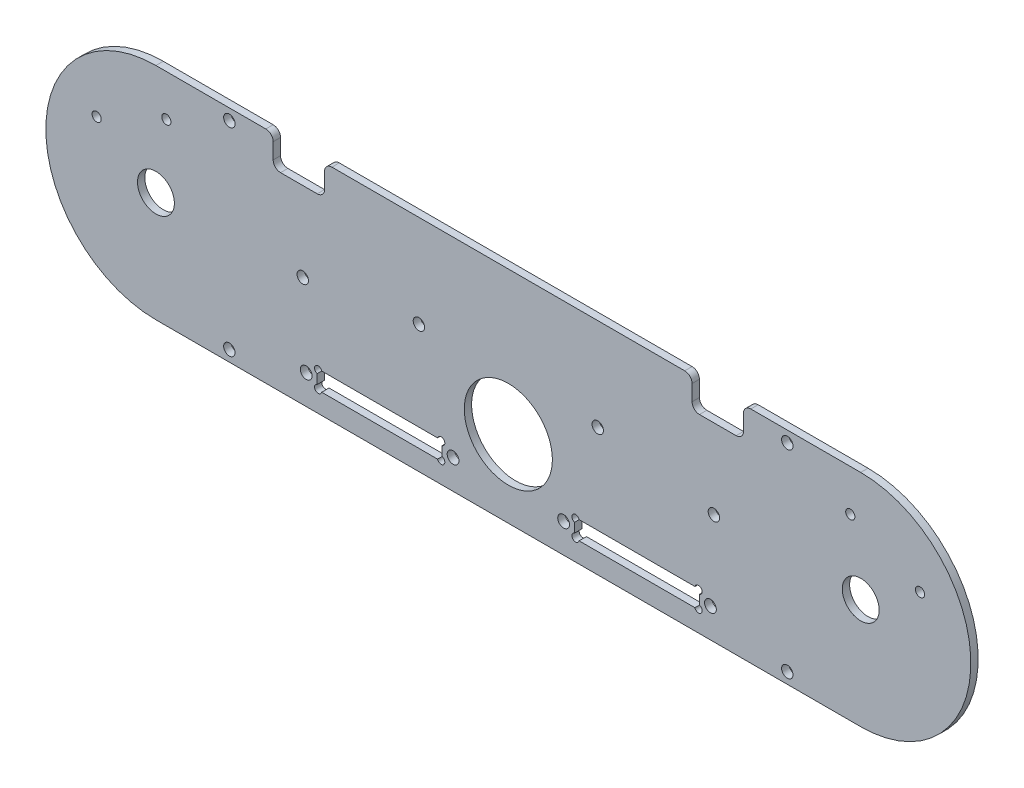
SolidWorks part; units mm, degrees
material "5052-O"
ref_plane "正面" through (0, 0, 0) normal (0, 0, 1) x (1, 0, 0)
ref_plane "平面" through (0, 0, 0) normal (0, 1, 0) x (1, 0, 0)
ref_plane "右側面" through (0, 0, 0) normal (1, 0, 0) x (0, 0, -1)
sketch "ｽｹｯﾁ1" plane through (0, 0, 0) normal (0, 0, 1) x (1, 0, 0)
  line L0 (-96, 0) -> (96, 0) construction
  line L1 (-96, 30) -> (96, 30) construction
  line L2 (-96, -30) -> (96, -30) construction
  line L4 (-96, -30) -> (96, -30)
  line L6 (96, 30) -> (-96, 30)
  arc A0 (-96, 30) -> (-96, -30) centre (-96, 0) ccw construction
  arc A1 (96, -30) -> (96, 30) centre (96, 0) ccw construction
  arc A2 (-96, 30) -> (-96, -30) centre (-96, 0) ccw
  arc A3 (96, -30) -> (96, 30) centre (96, 0) ccw
  point P2 (0, 0)
  dimension "D1" = 30
  dimension "D2" = 192
extrude "ﾎﾞｽ - 押し出し1" add sketch "ｽｹｯﾁ1" along normal blind 2
sketch "ｽｹｯﾁ2" plane through (0, 0, 2) normal (0, 0, 1) x (1, 0, 0)
  line L0 (-96, 0) -> (-56, 0) construction
  line L1 (0, 30) -> (0, -30) construction
  line L2 (-56, 0) -> (0, 0) construction
  line L3 (-96, 0) -> (-102.6562, 14.2743) construction
  line L4 (-76, 30) -> (-76, -30) construction
  line L9 (-112.1521, 9.8464) -> (-93.1604, 18.7023) construction
  line L10 (96, 0) -> (102.6562, 14.2743) construction
  line L11 (96, 30) -> (-96, 30) construction
  line L12 (-96, -30) -> (96, -30) construction
  line L13 (112.1521, 9.8464) -> (93.1604, 18.7023) construction
  line L14 (-96, -30) -> (96, -30) construction
  circle A1 centre (-56, 0) radius 16 construction
  circle A3 centre (-96, 0) radius 24 construction
  circle A8 centre (-56, 0) radius 1.55
  circle A9 centre (-96, 0) radius 11.5 construction
  circle A15 centre (56, 0) radius 1.55
  circle A16 centre (96, 0) radius 11.5 construction
  circle A17 centre (-76, 27) radius 1.55
  circle A18 centre (-76, -27) radius 1.55
  circle A19 centre (76, 27) radius 1.55
  circle A20 centre (76, -27) radius 1.55
  circle A21 centre (-24.3623, 4.8014) radius 16 construction
  circle A22 centre (-24.3623, 4.8014) radius 1.55
  circle A23 centre (24.3623, 4.8014) radius 1.55
  circle A25 centre (0, -9) radius 12
  circle A26 centre (-96, 0) radius 5.025
  circle A27 centre (96, 0) radius 5.025
  circle A28 centre (-112.1521, 9.8464) radius 1.25
  circle A29 centre (-93.1604, 18.7023) radius 1.25
  circle A30 centre (93.1604, 18.7023) radius 1.25
  circle A31 centre (112.1521, 9.8464) radius 1.25
  point P35 (0, 0)
  dimension "D1" = 48
  dimension "D2" = 32
  dimension "D3" = 10.05
  dimension "D5" = 20.955
  dimension "D6" = 23
  dimension "D10" = 3.1
  dimension "D11" = 3.1
  dimension "D12" = 3
  dimension "D13" = 3
  dimension "D8" = 24
  dimension "D17" = 2.5
  dimension "D18" = 21
  dimension "D14" = 20
  dimension "D15" = 96
  dimension "D16" = 25
  dimension "D9" = 15.75
extrude "ｶｯﾄ - 押し出し1" cut sketch "ｽｹｯﾁ2" against normal through all
sketch "ｽｹｯﾁ3" plane through (0, 0, 2) normal (0, 0, 1) x (1, 0, 0)
  line L0 (-55.0573, 24) -> (0, 24) construction
  line L1 (0, 30) -> (0, -28) construction
  line L2 (-18.0573, 26.5) -> (-52.0573, 26.5) construction
  line L3 (-18.0573, 26.5) -> (-18.0573, 21.5) construction
  line L4 (-18.0573, 21.5) -> (-52.0573, 21.5) construction
  line L5 (-52.0573, 26.5) -> (-52.0573, 21.5) construction
  line L6 (-18.0573, 26.5) -> (-52.0573, 21.5) construction
  line L7 (-18.0573, 21.5) -> (-52.0573, 26.5) construction
  line L8 (96, 30) -> (-96, 30) construction
  line L9 (18.0573, 21.5) -> (52.0573, 26.5) construction
  line L10 (18.0573, 26.5) -> (52.0573, 21.5) construction
  line L11 (55.0573, 24) -> (0, 24) construction
  line L12 (52.0573, 26.5) -> (52.0573, 21.5) construction
  line L13 (18.0573, 21.5) -> (52.0573, 21.5) construction
  line L14 (18.0573, 26.5) -> (18.0573, 21.5) construction
  line L15 (18.0573, 26.5) -> (52.0573, 26.5) construction
  line L16 (-125.9833, 1) -> (125.9833, 1) construction
  line L17 (55.0573, -22) -> (0, -22) construction
  line L18 (18.0573, -24.5) -> (52.0573, -19.5) construction
  line L19 (18.0573, -19.5) -> (52.0573, -24.5) construction
  line L20 (-18.0573, -19.5) -> (-52.0573, -24.5) construction
  line L21 (-18.0573, -24.5) -> (-52.0573, -19.5) construction
  line L22 (-55.0573, -22) -> (0, -22) construction
  line L23 (18.0573, -24.5) -> (52.0573, -24.5)
  line L24 (18.0573, -24.5) -> (18.0573, -19.5)
  line L25 (18.0573, -19.5) -> (52.0573, -19.5)
  line L26 (52.0573, -24.5) -> (52.0573, -19.5)
  line L27 (-52.0573, -24.5) -> (-52.0573, -19.5)
  line L28 (-18.0573, -19.5) -> (-52.0573, -19.5)
  line L29 (-18.0573, -24.5) -> (-18.0573, -19.5)
  line L30 (-18.0573, -24.5) -> (-52.0573, -24.5)
  circle A0 centre (-15.0573, 24) radius 1.6 construction
  circle A1 centre (-55.0573, 24) radius 1.6 construction
  circle A2 centre (15.0573, 24) radius 1.6 construction
  circle A3 centre (55.0573, 24) radius 1.6 construction
  circle A4 centre (55.0573, -22) radius 1.6
  circle A5 centre (15.0573, -22) radius 1.6
  circle A6 centre (-55.0573, -22) radius 1.6
  circle A7 centre (-15.0573, -22) radius 1.6
  arc A10 (-96, 30) -> (-96, -30) centre (-96, 0) ccw construction
  arc A11 (96, -30) -> (96, 30) centre (96, 0) ccw construction
  point P2 (-35.0573, 24)
  point P19 (35.0573, 24)
  point P39 (0, 1)
  point P46 (35.0573, -22)
  point P47 (-35.0573, -22)
  dimension "D6" = 3
  dimension "D7" = 3.2
  dimension "D4" = 30.1146
  dimension "D1" = 5
  dimension "D2" = 3
  dimension "D3" = 34
  dimension "D5" = 6
  dimension "D8" = 29
extrude "ｶｯﾄ - 押し出し2" cut sketch "ｽｹｯﾁ3" against normal through all
sketch "ｽｹｯﾁ4" plane through (0, 0, 2) normal (0, 0, 1) x (1, 0, 0)
  line L0 (0, 30) -> (0, 0) construction
  line L1 (-50.0573, 21.7) -> (-64.0573, 21.7)
  line L2 (-50.0573, 21.7) -> (-50.0573, 30)
  line L3 (-50.0573, 30) -> (-64.0573, 30)
  line L4 (-64.0573, 21.7) -> (-64.0573, 30)
  line L5 (-50.0573, 21.7) -> (-64.0573, 30) construction
  line L6 (-50.0573, 30) -> (-64.0573, 21.7) construction
  line L7 (96, 30) -> (-96, 30) construction
  line L8 (50.0573, 30) -> (64.0573, 30)
  line L9 (64.0573, 21.7) -> (64.0573, 30)
  line L10 (50.0573, 21.7) -> (64.0573, 21.7)
  line L11 (50.0573, 21.7) -> (50.0573, 30)
  point P0 (-57.0573, 25.85)
  dimension "D1" = 128.1146
  dimension "D2" = 14
  dimension "D3" = 8.3
extrude "ｶｯﾄ - 押し出し3" cut sketch "ｽｹｯﾁ4" against normal through all
fillet "ﾌｨﾚｯﾄ1" radius 2 8 edges at (64.0573, 30, 1) (64.0573, 21.7, 1) (50.0573, 21.7, 1) (50.0573, 30, 1) (-50.0573, 30, 1) (-50.0573, 21.7, 1) (-64.0573, 21.7, 1) (-64.0573, 30, 1)
sketch "ｽｹｯﾁ5" plane through (0, 0, 2) normal (0, 0, 1) x (1, 0, 0)
  line L0 (-52.0573, -19.5) -> (-18.0573, -24.5) construction
  line L1 (-18.0573, -19.5) -> (-52.0573, -19.5) construction
  line L2 (-18.3073, -19.75) -> (-51.8073, -19.75) construction
  line L3 (-18.3073, -19.75) -> (-18.3073, -24.25) construction
  line L4 (-18.3073, -24.25) -> (-51.8073, -24.25) construction
  line L5 (-51.8073, -19.75) -> (-51.8073, -24.25) construction
  line L6 (-18.3073, -19.75) -> (-51.8073, -24.25) construction
  line L7 (-18.3073, -24.25) -> (-51.8073, -19.75) construction
  line L8 (-52.0573, -19.5) -> (-52.0573, -24.5) construction
  line L9 (0, 0) -> (0, -30) construction
  line L10 (-96, -30) -> (96, -30) construction
  line L11 (18.3073, -24.25) -> (51.8073, -19.75) construction
  line L12 (18.3073, -19.75) -> (51.8073, -24.25) construction
  line L13 (51.8073, -19.75) -> (51.8073, -24.25) construction
  line L14 (18.3073, -24.25) -> (51.8073, -24.25) construction
  line L15 (18.3073, -19.75) -> (18.3073, -24.25) construction
  line L16 (18.3073, -19.75) -> (51.8073, -19.75) construction
  line L17 (52.0573, -19.5) -> (18.0573, -24.5) construction
  circle A0 centre (-51.8073, -19.75) radius 1
  circle A1 centre (-51.8073, -24.25) radius 1
  circle A2 centre (-18.3073, -24.25) radius 1
  circle A3 centre (-18.3073, -19.75) radius 1
  circle A4 centre (18.3073, -19.75) radius 1
  circle A5 centre (18.3073, -24.25) radius 1
  circle A6 centre (51.8073, -24.25) radius 1
  circle A7 centre (51.8073, -19.75) radius 1
  point P4 (-35.0573, -22)
  point P32 (35.0573, -22)
  dimension "D3" = 2
  dimension "D1" = 0.25
  dimension "D2" = 0.25
extrude "ｶｯﾄ - 押し出し4" cut sketch "ｽｹｯﾁ5" against normal through all
